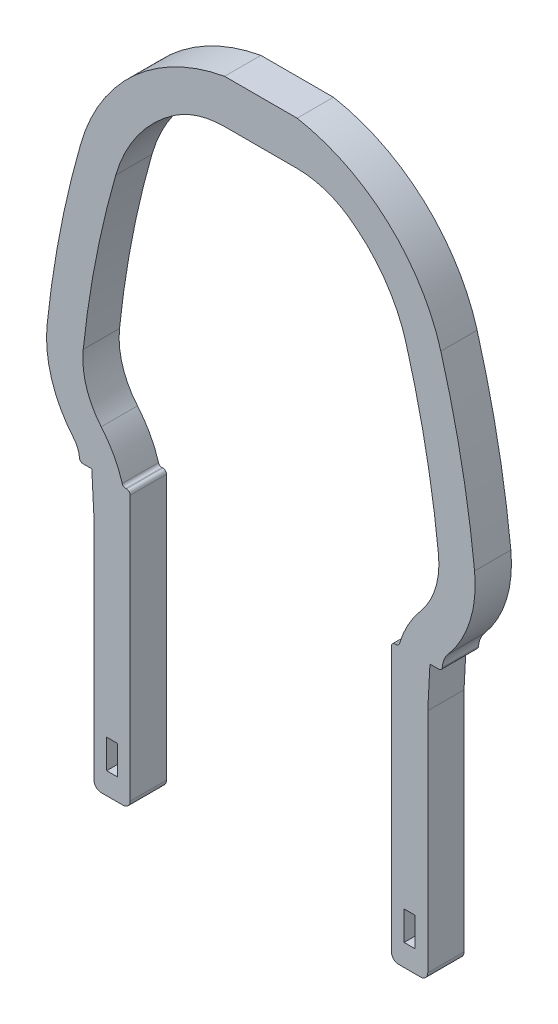
SolidWorks part; units mm, degrees
ref_plane "Front Plane" through (0, 0, 0) normal (0, 0, 1) x (1, 0, 0)
ref_plane "Top Plane" through (0, 0, 0) normal (0, 1, 0) x (1, 0, 0)
ref_plane "Right Plane" through (0, 0, 0) normal (1, 0, 0) x (0, 0, -1)
sketch "Sketch1" plane through (0, 0, 0) normal (0, 0, 1) x (1, 0, 0)
  line L0 (0, 0) -> (0, 50) construction
  line L1 (-18, -38) -> (-18, 0) construction
  line L2 (-23, 0) -> (-23, -38)
  line L3 (0, 0) -> (-23, 0) construction
  line L4 (0, 50) -> (-57.1655, 50) construction
  line L5 (-18, 0) -> (-30.8199, 22.2047) construction
  line L6 (-22.3301, -2.5) -> (-23, -38) construction
  line L7 (-23, -38) -> (-18, -38)
  line L8 (-18, -38) -> (-18, 0)
  line L9 (-5, 50) -> (0, 50)
  line L12 (23, -38) -> (18, -38)
  line L13 (18, -38) -> (18, 0)
  line L14 (5, 50) -> (0, 50)
  line L19 (-5, 56) -> (5, 56)
  line L20 (-5, 56) -> (-5, 50) construction
  line L21 (-25, 0) -> (-23, 0)
  line L22 (5, 56) -> (5, 50) construction
  line L23 (21.25, -6) -> (19.75, -6) construction
  line L24 (-21.25, -31) -> (-19.75, -31) construction
  line L25 (-21.25, -31) -> (-21.25, -35) construction
  line L26 (-21.25, -35) -> (-19.75, -35) construction
  line L27 (-19.75, -31) -> (-19.75, -35) construction
  line L28 (19.75, -31) -> (21.25, -31) construction
  line L29 (19.75, -31) -> (19.75, -35) construction
  line L30 (19.75, -35) -> (21.25, -35) construction
  line L31 (21.25, -31) -> (21.25, -35) construction
  line L32 (-21.25, -6) -> (-19.75, -6) construction
  line L33 (-21.25, -6) -> (-21.25, -10) construction
  line L34 (-21.25, -10) -> (-19.75, -10) construction
  line L35 (-19.75, -6) -> (-19.75, -10) construction
  line L36 (21.25, -6) -> (21.25, -10) construction
  line L37 (21.25, -10) -> (19.75, -10) construction
  line L38 (19.75, -6) -> (19.75, -10) construction
  line L39 (-19.75, -31) -> (-19.75, -35)
  line L40 (-21.25, -35) -> (-19.75, -35)
  line L41 (-21.25, -31) -> (-21.25, -35)
  line L42 (-21.25, -31) -> (-19.75, -31)
  line L43 (21.25, -31) -> (21.25, -35)
  line L44 (19.75, -35) -> (21.25, -35)
  line L45 (19.75, -31) -> (19.75, -35)
  line L46 (19.75, -31) -> (21.25, -31)
  line L47 (18, 0) -> (19, 0)
  line L48 (-18, 0) -> (-19, 0)
  line L49 (23, 0) -> (23, -38)
  line L50 (25, 0) -> (23, 0)
  arc A0 (-18, 0) -> (-22, 5.6708) centre (-51.1669, -19.1489) ccw construction
  arc A1 (-22, 5.6708) -> (-24.4794, 13.6708) centre (-13.8966, 12.5664) cw
  arc A2 (-12, 47.8224) -> (-5, 50) centre (-5, 37.6601) cw
  arc A3 (-24.4794, 13.6708) -> (-20, 36.7076) centre (108.2114, -0.1762) cw
  arc A4 (-20, 36.7076) -> (-12, 47.8224) centre (-0.4748, 31.0906) cw
  arc A5 (-22.3301, -2.5) -> (-25.8079, 2.4304) centre (-51.1669, -19.1489) ccw construction
  arc A6 (-25.8079, 2.4304) -> (-29.4524, 14.1897) centre (-13.8966, 12.5664) cw
  arc A7 (-29.4524, 14.1897) -> (-24.8051, 38.09) centre (108.2114, -0.1762) cw
  arc A8 (-24.8051, 38.09) -> (-14.8363, 51.9401) centre (-0.4748, 31.0906) cw
  arc A9 (-14.8363, 51.9401) -> (-5, 55) centre (-5, 37.6601) cw construction
  arc A10 (14.8363, 51.9401) -> (5, 55) centre (5, 37.6601) ccw construction
  arc A11 (24.8051, 38.09) -> (14.8363, 51.9401) centre (0.4748, 31.0906) ccw
  arc A12 (29.4524, 14.1897) -> (24.8051, 38.09) centre (-108.2114, -0.1762) ccw
  arc A13 (25.8079, 2.4304) -> (29.4524, 14.1897) centre (13.8966, 12.5664) ccw
  arc A15 (18, 0) -> (22, 5.6708) centre (51.1669, -19.1489) cw construction
  arc A16 (22, 5.6708) -> (24.4794, 13.6708) centre (13.8966, 12.5664) ccw
  arc A17 (24.4794, 13.6708) -> (20, 36.7076) centre (-108.2114, -0.1762) ccw
  arc A18 (20, 36.7076) -> (12, 47.8224) centre (0.4748, 31.0906) ccw
  arc A19 (12, 47.8224) -> (5, 50) centre (5, 37.6601) ccw
  arc A20 (-14.8363, 51.9401) -> (-5, 55) centre (-5, 37.6601) cw construction
  arc A23 (14.8363, 51.9401) -> (5, 56) centre (0.4748, 31.0906) ccw
  arc A25 (-14.8363, 51.9401) -> (-5, 56) centre (-0.4748, 31.0906) cw
  arc A26 (-25.8079, 2.4304) -> (-25, 0) centre (-28.4104, 0.2158) cw
  arc A27 (22, 5.6708) -> (19, 0) centre (33.2726, -3.9217) ccw
  arc A28 (-22, 5.6708) -> (-19, 0) centre (-33.2726, -3.9217) cw
  arc A29 (25.8079, 2.4304) -> (25, 0) centre (28.4104, 0.2158) ccw
  dimension "D13" = 5
  dimension "D11" = 1
  dimension "D1" = 18
  dimension "D2" = 50
  dimension "D3" = 5
  dimension "D4" = 31
  dimension "D5" = 60
  dimension "D6" = 5
  dimension "D7" = 12
  dimension "D8" = 8
  dimension "D9" = 8
  dimension "D10" = 22
  dimension "D12" = 3
  dimension "D15" = 2
  dimension "D16" = 6
  dimension "D17" = 4
  dimension "D18" = 1.5
  dimension "D19" = 1.75
  dimension "D21" = 6
  dimension "D22" = 2
extrude "Boss-Extrude2" add sketch "Sketch1" along normal blind 5
fillet "Fillet1" radius 0.5 6 edges at (-18, 0, 2.5) (18, 0, 2.5) (19, 0, 2.5) (-19, 0, 2.5) (-25, 0, 2.5) (25, 0, 2.5)
chamfer "Chamfer1" distance 0.3 angle 87 2 edges at (23, 0, 2.5) (-23, 0, 2.5)
fillet "Fillet2" radius 1 4 edges at (-23, -38, 2.5) (-18, -38, 2.5) (23, -38, 2.5) (18, -38, 2.5)
